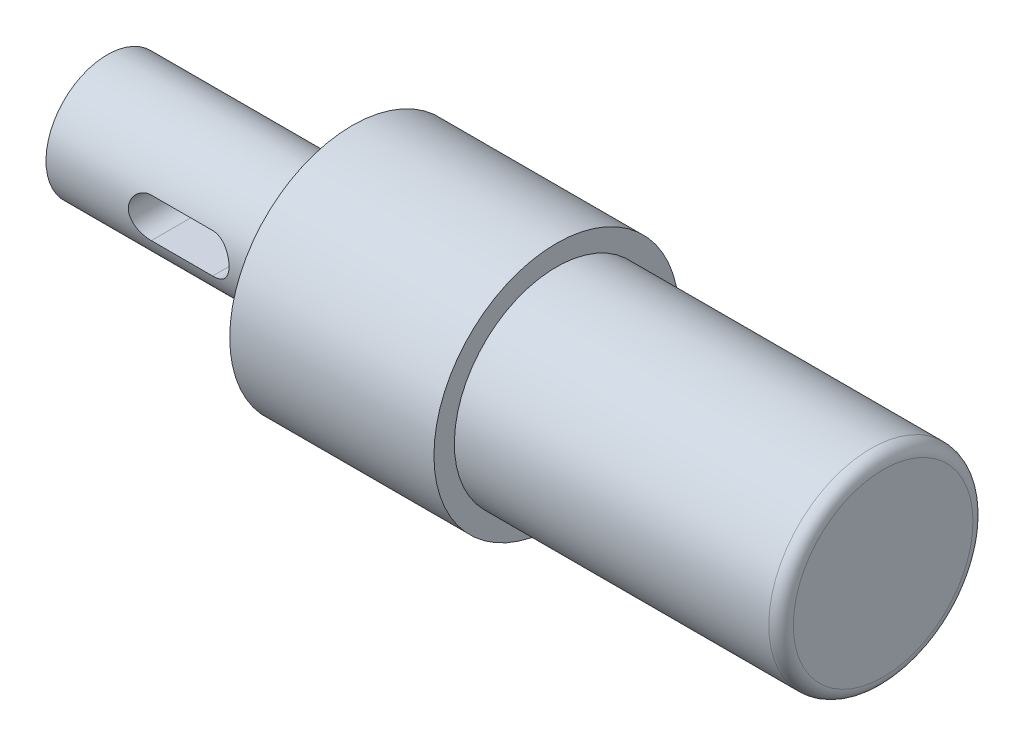
SolidWorks part; units mm, degrees
ref_plane "Front Plane" through (0, 0, 0) normal (0, 0, 1) x (1, 0, 0)
ref_plane "Top Plane" through (0, 0, 0) normal (0, 1, 0) x (1, 0, 0)
ref_plane "Right Plane" through (0, 0, 0) normal (1, 0, 0) x (0, 0, -1)
sketch "Sketch1" plane through (0, 0, 0) normal (0, 0, 1) x (1, 0, 0)
  line L0 (0, 0) -> (-60, 0)
  line L1 (-60, 0) -> (-60, 15)
  line L2 (-60, 15) -> (0, 15)
  line L3 (0, 15) -> (0, 30)
  line L4 (0, 30) -> (50, 30)
  line L5 (50, 30) -> (50, 25)
  line L6 (50, 25) -> (130, 25)
  line L7 (130, 25) -> (130, 0)
  line L8 (130, 0) -> (0, 0)
  line L9 (-83.216, 0) -> (157.5069, 0) construction
  dimension "D1" = 60
  dimension "D2" = 80
  dimension "D3" = 50
  dimension "D4" = 15
  dimension "D5" = 25
  dimension "D6" = 30
revolve "Revolve1" add sketch "Sketch1" angle 360 about L9
fillet "Fillet1" radius 3 1 edges at (130, -25, 0)
sketch "Sketch2" plane through (0, 0, 0) normal (0, 0, 1) x (1, 0, 0)
  line L1 (68.1685, 17.5598) -> (91.1708, 17.5598)
  line L2 (68.1685, 17.5598) -> (68.1685, -14.4791)
  line L3 (68.1685, -14.4791) -> (91.1708, -14.4791)
  line L4 (91.1708, 17.5598) -> (91.1708, -14.4791)
  line L5 (68.1685, 17.5598) -> (91.1708, -14.4791) construction
  line L6 (68.1685, -14.4791) -> (91.1708, 17.5598) construction
  circle A0 centre (79.6696, 1.5403) radius 6.9949
  point P0 (79.6696, 1.5403)
extrude "Cut-Extrude1" cut sketch "Sketch2" against normal blind 30 contours L2 L1 L4 L3
sketch "Sketch3" plane through (0, 0, 0) normal (0, 0, -1) x (-1, 0, 0)
  circle A0 centre (-79.9383, 1.1392) radius 6.1783
extrude "Cut-Extrude2" cut sketch "Sketch3" against normal blind 20
sketch "Sketch4" plane through (0, 0, 0) normal (0, 0, 1) x (1, 0, 0)
  circle A0 centre (24.0123, 2.978) radius 10
  dimension "D1" = 20
extrude "Cut-Extrude3" cut sketch "Sketch4" against normal blind 30
sketch "Sketch6" plane through (0, 0, 0) normal (0, 0, 1) x (1, 0, 0)
  line L0 (-35, 0) -> (-20, 0) construction
  line L1 (-35, 4.8264) -> (-20, 4.8264)
  line L2 (-35, -4.8264) -> (-20, -4.8264)
  line L3 (-60, 15) -> (-60, -15) construction
  arc A0 (-35, 4.8264) -> (-35, -4.8264) centre (-35, 0) ccw
  arc A1 (-20, -4.8264) -> (-20, 4.8264) centre (-20, 0) ccw
  point P3 (-27.5, 0)
  dimension "D1" = 15
  dimension "D2" = 25
extrude "Cut-Extrude4" cut sketch "Sketch6" against normal blind 33 and the other way through all
